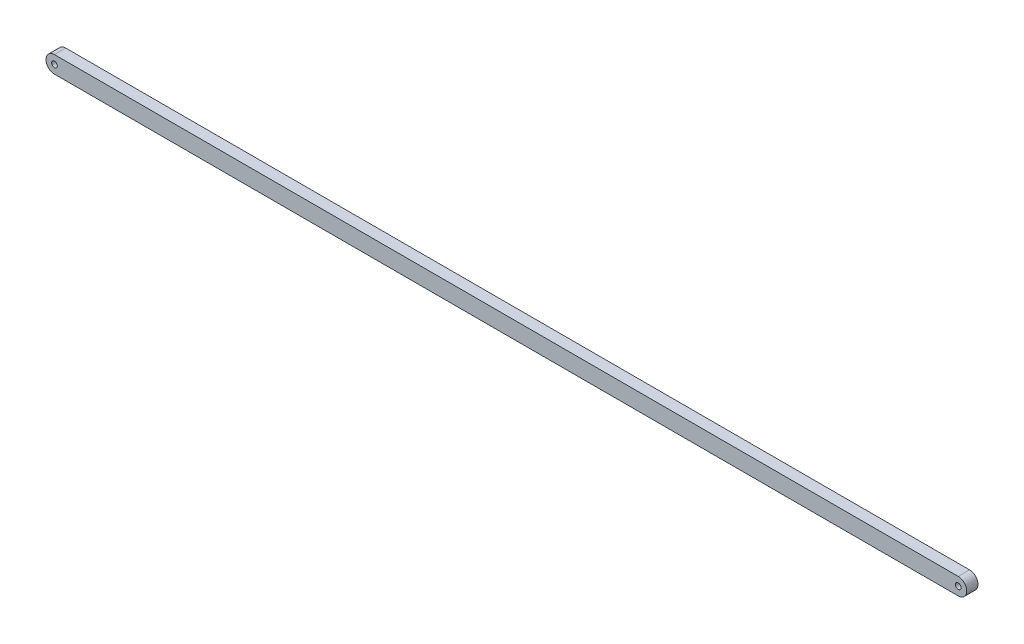
SolidWorks part; units mm, degrees
material "AISI 304"
ref_plane "前视基准面" through (0, 0, 0) normal (0, 0, 1) x (1, 0, 0)
ref_plane "上视基准面" through (0, 0, 0) normal (0, 1, 0) x (1, 0, 0)
ref_plane "右视基准面" through (0, 0, 0) normal (1, 0, 0) x (0, 0, -1)
sketch "草图1" plane through (0, 0, 0) normal (0, 0, 1) x (1, 0, 0)
  line L0 (0, 1.5) -> (160, 1.5)
  line L1 (160, -1.5) -> (0, -1.5)
  circle A0 centre (0, 0) radius 0.5
  arc A1 (0, 1.5) -> (0, -1.5) centre (0, 0) ccw
  circle A2 centre (160, 0) radius 0.5
  arc A3 (160, -1.5) -> (160, 1.5) centre (160, 0) ccw
  dimension "D2" = 1
  dimension "D3" = 3
  dimension "D1" = 160
extrude "凸台-拉伸1" add sketch "草图1" along normal blind 2 contours L0 A3 L1 A1
sketch "草图2" plane through (0, 0, 0) normal (0, 0, -1) x (-1, 0, 0)
  circle A0 centre (-160, 0) radius 0.5
  circle A1 centre (0, 0) radius 0.5
extrude "切除-拉伸1" cut sketch "草图2" against normal blind 2
